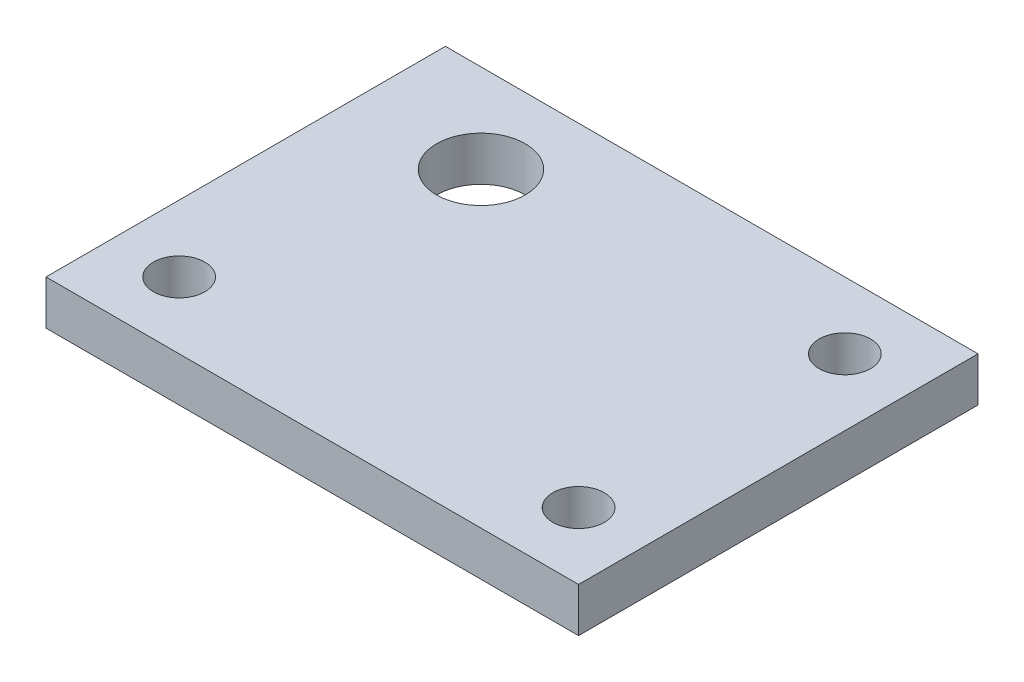
SolidWorks part; units mm, degrees
ref_plane "Front Plane" through (0, 0, 0) normal (0, 0, 1) x (1, 0, 0)
ref_plane "Top Plane" through (0, 0, 0) normal (0, 1, 0) x (1, 0, 0)
ref_plane "Right Plane" through (0, 0, 0) normal (1, 0, 0) x (0, 0, -1)
sketch "Sketch1" plane through (0, 0, 0) normal (0, 1, 0) x (1, 0, 0)
  line L1 (-19.05, -14.2875) -> (19.05, -14.2875)
  line L2 (-19.05, -14.2875) -> (-19.05, 14.2875)
  line L3 (-19.05, 14.2875) -> (19.05, 14.2875)
  line L4 (19.05, -14.2875) -> (19.05, 14.2875)
  line L5 (-19.05, -14.2875) -> (19.05, 14.2875) construction
  line L6 (-19.05, 14.2875) -> (19.05, -14.2875) construction
  circle A1 centre (-10.16, 7.9375) radius 3.175
  point P0 (-10.16, 7.9375)
  point P2 (0, 3.175)
  point P7 (0, 0)
  point P9 (0, 0)
  point P10 (0, 0)
  point P11 (0, 0)
  point P12 (0, 0)
  point P13 (0, 0)
  point P14 (0, 0)
  point P15 (0, 0)
  point P16 (0.7601, 6.9914)
  point P18 (0, 0)
  point P19 (0, 0)
  point P20 (0, 3.175)
  point P21 (0, 0)
  point P22 (-0.835, 3.175)
  dimension "D4" = 6.35
  dimension "D1" = 38.1
  dimension "D2" = 28.575
  dimension "D3" = 6.35
  dimension "D5" = 8.89
extrude "Boss-Extrude1" add sketch "Sketch1" along normal blind 3.175
sketch "Sketch2" plane through (0, 3.175, 0) normal (0, 1, 0) x (1, 0, 0)
  line L0 (-19.05, 14.2875) -> (-19.05, -14.2875) construction
  line L1 (-19.05, -14.2875) -> (19.05, -14.2875) construction
  line L2 (19.05, -14.2875) -> (19.05, 14.2875) construction
  line L3 (19.05, 14.2875) -> (-19.05, 14.2875) construction
  circle A0 centre (-14.2875, -9.525) radius 1.8415
  circle A1 centre (14.2875, -9.525) radius 1.8415
  circle A2 centre (14.2875, 9.525) radius 1.8415
  point P6 (0, 0)
  point P7 (0, 0)
  point P10 (11.5527, -7.1541)
  point P15 (11.1125, 5.5274)
  dimension "D2" = 3.683
  dimension "D1" = 4.7625
  dimension "D3" = 4.7625
  dimension "D4" = 4.7625
  dimension "D5" = 4.7625
extrude "Cut-Extrude1" cut sketch "Sketch2" against normal through all
